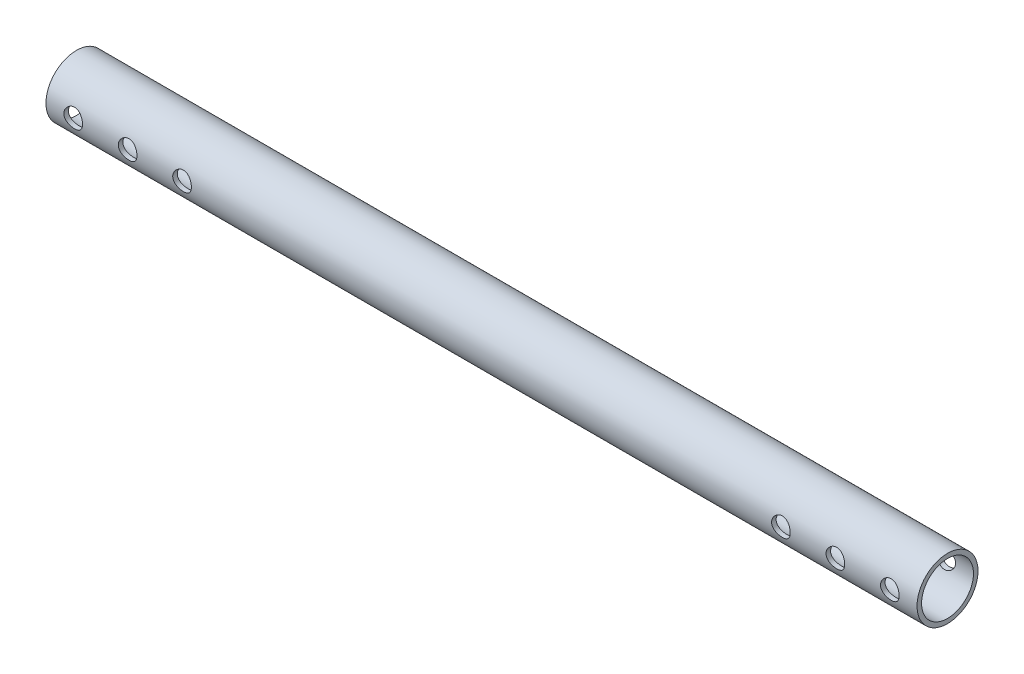
SolidWorks part; units mm, degrees
ref_plane "Front Plane" through (0, 0, 0) normal (0, 0, 1) x (1, 0, 0)
ref_plane "Top Plane" through (0, 0, 0) normal (0, 1, 0) x (1, 0, 0)
ref_plane "Right Plane" through (0, 0, 0) normal (1, 0, 0) x (0, 0, -1)
sketch "Sketch1" plane through (0, 0, 0) normal (1, 0, 0) x (0, 0, -1)
  circle A0 centre (0, 0) radius 10.668
  circle A1 centre (0, 0) radius 9.0805
  dimension "D1" = 1.5875
  dimension "D2" = 21.336
extrude "Boss-Extrude1" add sketch "Sketch1" along normal blind 304.8
ref_plane "Plane1" through (0, 0, 10) normal (0, 0, 1) x (1, 0, 0)
sketch "Sketch2" plane through (0, 0, 10) normal (0, 0, 1) x (1, 0, 0)
  line L0 (0, 0) -> (304.8, 0) construction
  line L1 (304.8, -10.668) -> (304.8, 10.668) construction
  line L2 (152.4, 10.668) -> (152.4, -10.668) construction
  line L3 (304.8, 10.668) -> (0, 10.668) construction
  circle A0 centre (9.525, 0) radius 3.2639
  circle A1 centre (28.575, 0) radius 3.2639
  circle A2 centre (47.625, 0) radius 3.2639
  circle A3 centre (295.275, 0) radius 3.2639
  circle A4 centre (276.225, 0) radius 3.2639
  circle A5 centre (257.175, 0) radius 3.2639
  point P15 (152.4, 0)
  dimension "D1" = 9.525
  dimension "D2" = 3
extrude "Cut-Extrude1" cut sketch "Sketch2" against normal through all and the other way through all
equation "\"1f\"=10"
